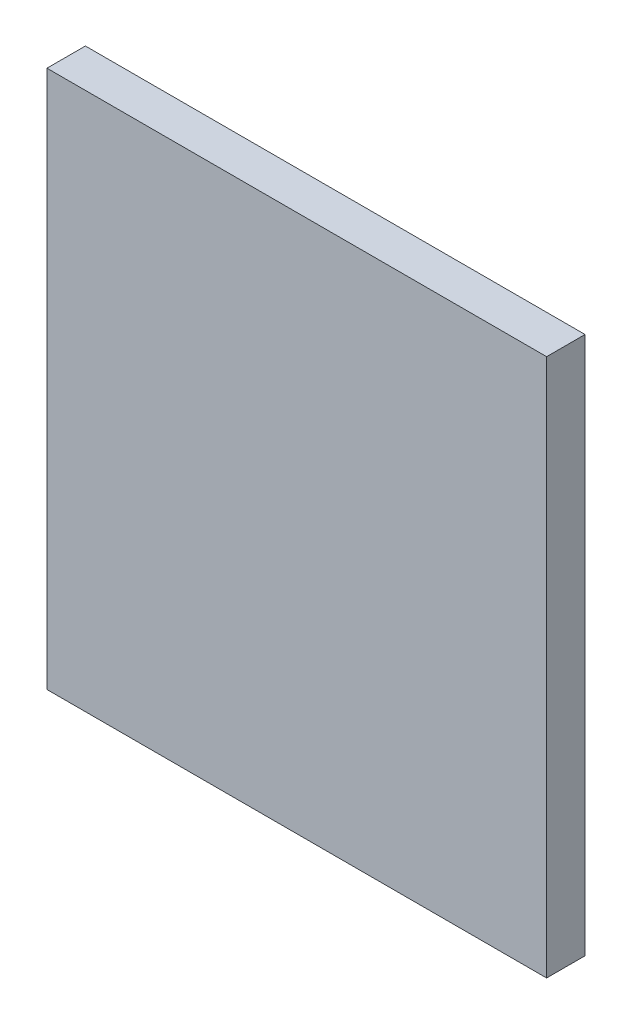
SolidWorks part; units mm, degrees
ref_plane "Alzado" through (0, 0, 0) normal (0, 0, 1) x (1, 0, 0)
ref_plane "Planta" through (0, 0, 0) normal (0, 1, 0) x (1, 0, 0)
ref_plane "Vista lateral" through (0, 0, 0) normal (1, 0, 0) x (0, 0, -1)
sketch "Croquis1" plane through (0, 0, 0) normal (0, 0, 1) x (1, 0, 0)
  line L1 (-29.2384, 23.8564) -> (35.7616, 23.8564)
  line L2 (-29.2384, 23.8564) -> (-29.2384, -46.1436)
  line L3 (-29.2384, -46.1436) -> (35.7616, -46.1436)
  line L4 (35.7616, 23.8564) -> (35.7616, -46.1436)
  dimension "D1" = 65
  dimension "D2" = 70
extrude "Saliente-Extruir1" add sketch "Croquis1" along normal blind 5
